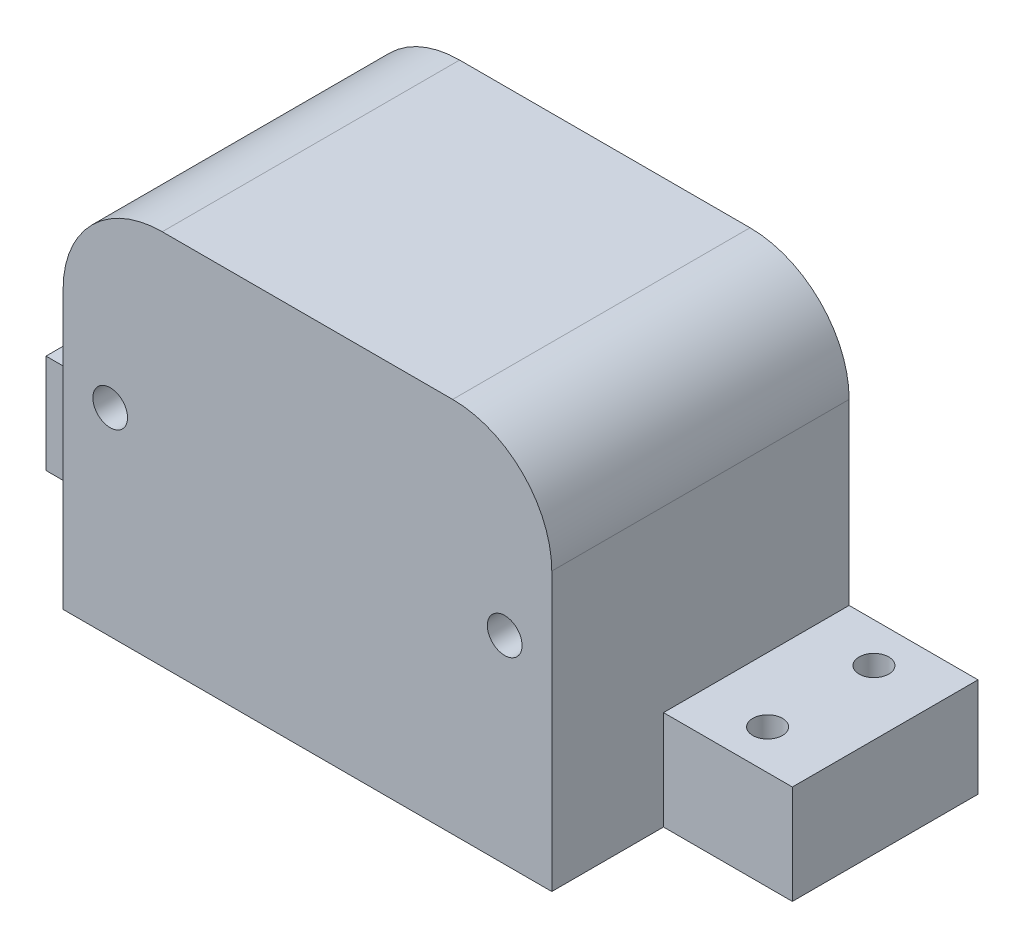
SolidWorks part; units mm, degrees
ref_plane "Спереди" through (0, 0, 0) normal (0, 0, 1) x (1, 0, 0)
ref_plane "Сверху" through (0, 0, 0) normal (0, 1, 0) x (1, 0, 0)
ref_plane "Справа" through (0, 0, 0) normal (1, 0, 0) x (0, 0, -1)
other "Configuration Table"
sketch "Эскиз2" plane through (0, 0, 0) normal (0, 0, 1) x (1, 0, 0)
  line L0 (-24.65, 1) -> (24.65, 1) construction
  line L1 (-24.65, -19) -> (24.65, -19)
  line L2 (-24.65, -19) -> (-24.65, 19)
  line L3 (-24.65, 19) -> (24.65, 19)
  line L4 (24.65, -19) -> (24.65, 19)
  line L5 (-24.65, -19) -> (24.65, 19) construction
  line L6 (-24.65, 19) -> (24.65, -19) construction
  line L7 (0, 19) -> (0, -19) construction
  line L8 (37.65, -9) -> (37.65, -19)
  line L9 (-24.65, -9) -> (-37.65, -9)
  line L10 (-24.65, -9) -> (-24.65, -19)
  line L11 (-24.65, -19) -> (-37.65, -19)
  line L12 (-37.65, -9) -> (-37.65, -19)
  line L13 (24.65, -19) -> (37.65, -19)
  line L14 (24.65, -9) -> (24.65, -19)
  line L15 (24.65, -9) -> (37.65, -9)
  circle A0 centre (-19.9, 1) radius 1.75
  circle A1 centre (19.9, 1) radius 1.75
  point P0 (0, 0)
  point P10 (-21.65, 1)
  point P15 (21.65, 1)
  dimension "D4" = 3.5
  dimension "D5" = 3
  dimension "D1" = 49.3
  dimension "D2" = 38
  dimension "D3" = 20
  dimension "D6" = 13
  dimension "D7" = 10
extrude "Бобышка-Вытянуть1" add sketch "Эскиз2" along normal blind 30 contours L1 L4 L3 L2 A0 A1 | L9 L12 L11 L2 | L15 L4 L13 L8
sketch "Эскиз3" plane through (0, -19, 0) normal (0, -1, 0) x (1, 0, 0)
  line L0 (0, 30) -> (0, 0) construction
  line L1 (-37.65, 30) -> (37.65, 30) construction
sketch "Эскиз4" plane through (0, 0, 30) normal (0, 0, 1) x (1, 0, 0)
  line L0 (19.9, 1) -> (-19.9, 1) construction
  line L1 (0, 19) -> (0, -18.9522) construction
  line L2 (-24.65, 19) -> (24.65, 19) construction
  point P9 (0, 1)
fillet "Скругление2" radius 10 2 edges at (24.65, 19, 15) (-24.65, 19, 15)
sketch "Эскиз5" plane through (0, -9, 0) normal (0, 1, 0) x (1, 0, 0)
  line L1 (0, 0) -> (0, -30) construction
  line L2 (-37.65, -30) -> (-37.65, 0) construction
  line L5 (-14.65, 0) -> (14.65, 0) construction
  line L6 (-24.65, -30) -> (-37.65, -30)
  line L7 (-24.65, -30) -> (-24.65, -18.728)
  line L8 (-24.65, -18.728) -> (-37.65, -18.728)
  line L9 (-37.65, -30) -> (-37.65, -18.728)
  line L10 (-31.15, 0) -> (-31.15, -30) construction
  line L11 (-24.65, 0) -> (-37.65, 0) construction
  line L12 (31.15, 0) -> (31.15, -30) construction
  line L13 (37.65, -30) -> (37.65, -18.728)
  line L14 (24.65, -18.728) -> (37.65, -18.728)
  line L15 (24.65, -30) -> (24.65, -18.728)
  line L16 (24.65, -30) -> (37.65, -30)
  circle A0 centre (-31.15, -4) radius 1.5
  circle A1 centre (-31.15, -14.728) radius 1.5
  circle A2 centre (31.15, -14.728) radius 1.5
  circle A3 centre (31.15, -4) radius 1.5
  dimension "D1" = 3
  dimension "D2" = 3
  dimension "D3" = 4
  dimension "D4" = 4
  dimension "D5" = 11.272
extrude "Вырез-Вытянуть2" cut sketch "Эскиз5" against normal blind 20
